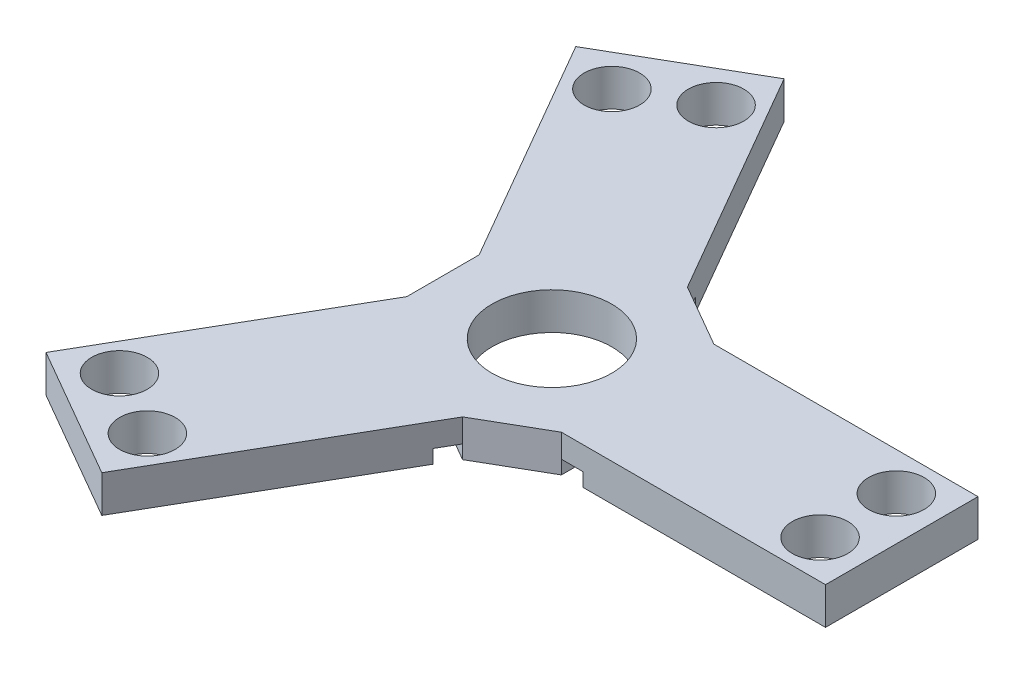
SolidWorks part; units mm, degrees
material "Oak"
ref_plane "Front Plane" through (0, 0, 0) normal (0, 0, 1) x (1, 0, 0)
ref_plane "Top Plane" through (0, 0, 0) normal (0, 1, 0) x (1, 0, 0)
ref_plane "Right Plane" through (0, 0, 0) normal (1, 0, 0) x (0, 0, -1)
sketch "Sketch1" plane through (0, 0, 0) normal (0, 1, 0) x (1, 0, 0)
  line L1 (20, 0) -> (-10, 17.3205)
  line L2 (-10, 17.3205) -> (-10, -17.3205)
  line L3 (-10, -17.3205) -> (20, 0)
  line L4 (7.8756, 7) -> (32.1244, 7)
  line L5 (7.8756, 7) -> (7.8756, -7)
  line L6 (7.8756, -7) -> (32.1244, -7)
  line L7 (32.1244, 7) -> (32.1244, -7)
  line L8 (2.1244, -10.3205) -> (-10, -3.3205)
  line L9 (2.1244, -10.3205) -> (-10, -31.3205)
  line L10 (-10, -31.3205) -> (-22.1244, -24.3205)
  line L11 (-10, -3.3205) -> (-22.1244, -24.3205)
  line L12 (-10, 3.3205) -> (2.1244, 10.3205)
  line L13 (-10, 3.3205) -> (-22.1244, 24.3205)
  line L14 (-22.1244, 24.3205) -> (-10, 31.3205)
  line L15 (2.1244, 10.3205) -> (-10, 31.3205)
  circle A0 centre (0, 0) radius 10 construction
  circle A1 centre (0, 0) radius 5.5
  point P7 (20, 7)
  point P23 (0, 0)
  dimension "D1" = 20
  dimension "D3" = 11
  dimension "D4" = 14
  dimension "D2" = 3
extrude "Boss-Extrude1" add sketch "Sketch1" along normal blind 3.4 contours L12 L2 L8 L3 L5 L1 A1 | L1 L5 L3 | L7 L4 L1 L3 L6 | L3 L8 L2 | L2 L11 L10 L9 L3 | L2 L12 L1 | L1 L15 L14 L13 L2
sketch "Sketch3" plane through (0, 3.4, 0) normal (0, 1, 0) x (1, 0, 0)
  line L0 (0, 0) -> (28.1244, 0) construction
  line L1 (28.1244, 0) -> (28.1244, 3.5) construction
  line L2 (28.1244, 0) -> (28.1244, -3.5) construction
  line L3 (32.1244, 7) -> (32.1244, -7) construction
  line L4 (0, 0) -> (-14.0622, -24.3564) construction
  line L5 (-14.0622, -24.3564) -> (-17.0933, -22.6064) construction
  line L6 (-14.0622, -24.3564) -> (-11.0311, -26.1064) construction
  line L7 (0, 0) -> (-14.0622, 24.3564) construction
  line L8 (-14.0622, 24.3564) -> (-11.0311, 26.1064) construction
  line L9 (-14.0622, 24.3564) -> (-17.0933, 22.6064) construction
  circle A0 centre (28.1244, 3.5) radius 2.55
  circle A1 centre (28.1244, -3.5) radius 2.55
  circle A2 centre (-11.0311, -26.1064) radius 2.55
  circle A3 centre (-17.0933, -22.6064) radius 2.55
  circle A4 centre (-17.0933, 22.6064) radius 2.55
  circle A5 centre (-11.0311, 26.1064) radius 2.55
  point P22 (0, 0)
  dimension "D1" = 5.1
  dimension "D2" = 4
  dimension "D3" = 3.5
  dimension "D4" = 3
extrude "Cut-Extrude1" cut sketch "Sketch3" against normal through all
sketch "Sketch4" plane through (0, 0, 0) normal (0, -1, 0) x (1, 0, 0)
  line L0 (7.8756, -7) -> (7.8756, 7)
  line L1 (7.8756, 7) -> (9.8756, 7)
  line L2 (7.8756, 7) -> (32.1244, 7) construction
  line L3 (9.8756, 7) -> (9.8756, -7)
  line L4 (7.8756, -7) -> (32.1244, -7) construction
  line L5 (9.8756, -7) -> (7.8756, -7)
  line L6 (-11, -5.0526) -> (-10, -3.3205)
  line L7 (-10, -3.3205) -> (2.1244, -10.3205)
  line L8 (2.1244, -10.3205) -> (1.1244, -12.0526)
  line L9 (1.1244, -12.0526) -> (-11, -5.0526)
  line L10 (1.1244, 12.0526) -> (2.1244, 10.3205)
  line L11 (2.1244, 10.3205) -> (-10, 3.3205)
  line L12 (-10, 3.3205) -> (-11, 5.0526)
  line L13 (-11, 5.0526) -> (1.1244, 12.0526)
  point P4 (0, 0)
  point P21 (0, 0)
  dimension "D1" = 2
  dimension "D2" = 3
extrude "Cut-Extrude2" cut sketch "Sketch4" against normal blind 1.25
